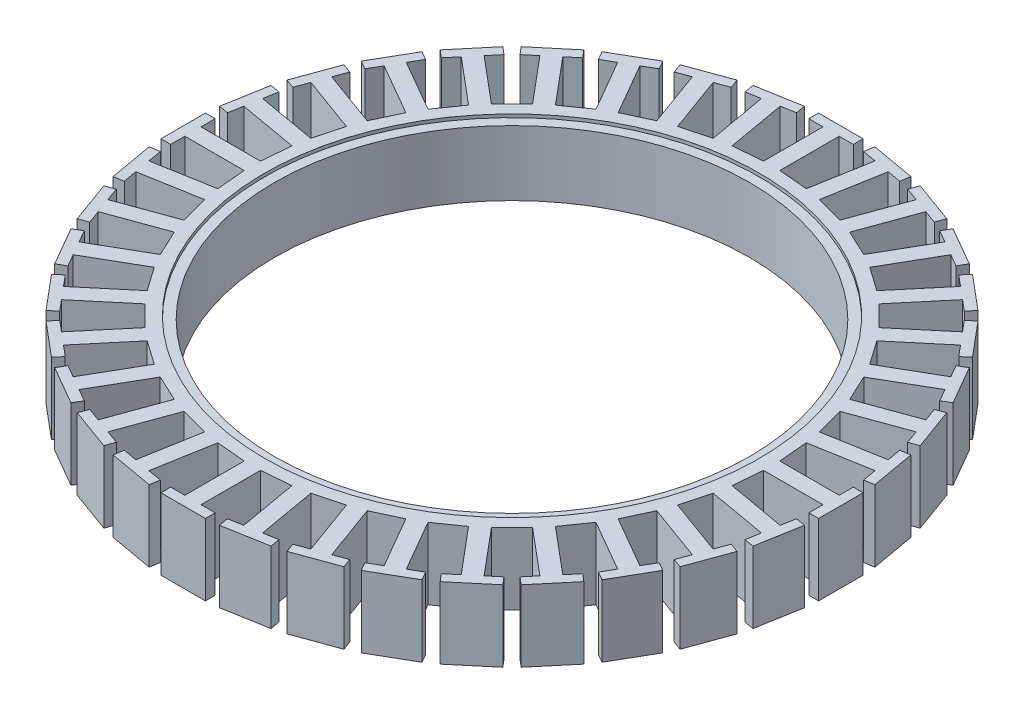
SolidWorks part; units mm, degrees
ref_plane "Front Plane" through (0, 0, 0) normal (0, 0, 1) x (1, 0, 0)
ref_plane "Top Plane" through (0, 0, 0) normal (0, 1, 0) x (1, 0, 0)
ref_plane "Right Plane" through (0, 0, 0) normal (1, 0, 0) x (0, 0, -1)
sketch "Sketch1" plane through (0, 0, 0) normal (0, 1, 0) x (1, 0, 0)
  circle A0 centre (0, 0) radius 29.25
  circle A1 centre (0, 0) radius 30.45
  dimension "D1" = 58.5
  dimension "D2" = 1.2
extrude "Boss-Extrude1" add sketch "Sketch1" along normal mid plane 8
sketch "Sketch2" plane through (0, 0, 0) normal (0, 1, 0) x (1, 0, 0)
  line L0 (0, 0) -> (0, 40.5) construction
  line L1 (-3.5433, 40.5) -> (-10.5222, 39.2694)
  line L2 (-10.5222, 39.2694) -> (-17.1814, 36.8457)
  line L3 (-17.1814, 36.8457) -> (-23.3186, 33.3024)
  line L4 (-23.3186, 33.3024) -> (-28.7472, 28.7472)
  line L5 (-28.7472, 28.7472) -> (-33.3024, 23.3186)
  line L6 (-33.3024, 23.3186) -> (-36.8457, 17.1814)
  line L7 (-36.8457, 17.1814) -> (-39.2694, 10.5222)
  line L8 (-39.2694, 10.5222) -> (-40.5, 3.5433)
  line L9 (-40.5, 3.5433) -> (-40.5, -3.5433)
  line L10 (-40.5, -3.5433) -> (-39.2694, -10.5222)
  line L11 (-39.2694, -10.5222) -> (-36.8457, -17.1814)
  line L12 (-36.8457, -17.1814) -> (-33.3024, -23.3186)
  line L13 (-33.3024, -23.3186) -> (-28.7472, -28.7472)
  line L14 (-28.7472, -28.7472) -> (-23.3186, -33.3024)
  line L15 (-23.3186, -33.3024) -> (-17.1814, -36.8457)
  line L16 (-17.1814, -36.8457) -> (-10.5222, -39.2694)
  line L17 (-10.5222, -39.2694) -> (-3.5433, -40.5)
  line L18 (-3.5433, -40.5) -> (3.5433, -40.5)
  line L19 (3.5433, -40.5) -> (10.5222, -39.2694)
  line L20 (10.5222, -39.2694) -> (17.1814, -36.8457)
  line L21 (17.1814, -36.8457) -> (23.3186, -33.3024)
  line L22 (23.3186, -33.3024) -> (28.7472, -28.7472)
  line L23 (28.7472, -28.7472) -> (33.3024, -23.3186)
  line L24 (33.3024, -23.3186) -> (36.8457, -17.1814)
  line L25 (36.8457, -17.1814) -> (39.2694, -10.5222)
  line L26 (39.2694, -10.5222) -> (40.5, -3.5433)
  line L27 (40.5, -3.5433) -> (40.5, 3.5433)
  line L28 (40.5, 3.5433) -> (39.2694, 10.5222)
  line L29 (39.2694, 10.5222) -> (36.8457, 17.1814)
  line L30 (36.8457, 17.1814) -> (33.3024, 23.3186)
  line L31 (33.3024, 23.3186) -> (28.7472, 28.7472)
  line L32 (28.7472, 28.7472) -> (23.3186, 33.3024)
  line L33 (23.3186, 33.3024) -> (17.1814, 36.8457)
  line L34 (17.1814, 36.8457) -> (10.5222, 39.2694)
  line L35 (10.5222, 39.2694) -> (3.5433, 40.5)
  line L36 (3.5433, 40.5) -> (-3.5433, 40.5)
  circle A1 centre (0, 0) radius 30.45
  circle A2 centre (0, 0) radius 40.5 construction
  circle A3 centre (0, 0) radius 30.45 construction
  dimension "D1" = 81
extrude "Boss-Extrude2" add sketch "Sketch2" along normal mid plane 8.8
sketch "Sketch4" plane through (0, 4.4, 0) normal (0, 1, 0) x (1, 0, 0)
  line L0 (0, 0) -> (0, 40.5) construction
  line L1 (3.5433, 40.5) -> (-3.5433, 40.5) construction
  line L2 (0, 0) -> (3.5433, 40.5) construction
  line L3 (1, 39.3) -> (2.7402, 39.3)
  line L4 (1, 39.3) -> (1, 31.9846)
  line L5 (10.5222, 39.2694) -> (3.5433, 40.5) construction
  line L6 (1, 31.9846) -> (4.5693, 31.6723)
  line L7 (4.5693, 31.6723) -> (5.8396, 38.8766)
  line L8 (2.7402, 39.3) -> (2.7402, 40.5)
  line L9 (2.7402, 40.5) -> (3.5433, 40.5)
  line L10 (3.5433, 40.5) -> (4.3341, 40.3606)
  line L11 (4.3341, 40.3606) -> (4.1258, 39.1788)
  line L12 (4.1258, 39.1788) -> (5.8396, 38.8766)
  line L13 (7.8092, 38.5293) -> (9.523, 38.2271)
  line L14 (7.8092, 38.5293) -> (6.5389, 31.325)
  line L15 (6.5389, 31.325) -> (9.9997, 30.3977)
  line L16 (9.9997, 30.3977) -> (12.5017, 37.2719)
  line L17 (9.523, 38.2271) -> (9.7314, 39.4089)
  line L18 (9.7314, 39.4089) -> (10.5222, 39.2694)
  line L19 (10.5222, 39.2694) -> (11.2768, 38.9948)
  line L20 (11.2768, 38.9948) -> (10.8664, 37.8671)
  line L21 (10.8664, 37.8671) -> (12.5017, 37.2719)
  line L22 (14.3811, 36.5879) -> (16.0164, 35.9927)
  line L23 (14.3811, 36.5879) -> (11.8791, 29.7136)
  line L24 (11.8791, 29.7136) -> (15.1263, 28.1994)
  line L25 (15.1263, 28.1994) -> (18.784, 34.5348)
  line L26 (16.0164, 35.9927) -> (16.4268, 37.1203)
  line L27 (16.4268, 37.1203) -> (17.1814, 36.8457)
  line L28 (17.1814, 36.8457) -> (17.8769, 36.4441)
  line L29 (17.8769, 36.4441) -> (17.2769, 35.4049)
  line L30 (17.2769, 35.4049) -> (18.784, 34.5348)
  line L31 (20.516, 33.5348) -> (22.0231, 32.6647)
  line L32 (20.516, 33.5348) -> (16.8583, 27.1994)
  line L33 (16.8583, 27.1994) -> (19.7932, 25.1444)
  line L34 (19.7932, 25.1444) -> (24.4955, 30.7483)
  line L35 (22.0231, 32.6647) -> (22.6231, 33.7039)
  line L36 (22.6231, 33.7039) -> (23.3186, 33.3024)
  line L37 (23.3186, 33.3024) -> (23.9338, 32.7862)
  line L38 (23.9338, 32.7862) -> (23.1624, 31.8669)
  line L39 (23.1624, 31.8669) -> (24.4955, 30.7483)
  line L40 (26.0276, 29.4628) -> (27.3607, 28.3442)
  line L41 (26.0276, 29.4628) -> (21.3253, 23.8588)
  line L42 (21.3253, 23.8588) -> (23.8588, 21.3253)
  line L43 (23.8588, 21.3253) -> (29.4628, 26.0276)
  line L44 (27.3607, 28.3442) -> (28.132, 29.2634)
  line L45 (28.132, 29.2634) -> (28.7472, 28.7472)
  line L46 (28.7472, 28.7472) -> (29.2634, 28.132)
  line L47 (29.2634, 28.132) -> (28.3442, 27.3607)
  line L48 (28.3442, 27.3607) -> (29.4628, 26.0276)
  line L49 (30.7483, 24.4955) -> (31.8669, 23.1624)
  line L50 (30.7483, 24.4955) -> (25.1444, 19.7932)
  line L51 (25.1444, 19.7932) -> (27.1994, 16.8583)
  line L52 (27.1994, 16.8583) -> (33.5348, 20.516)
  line L53 (31.8669, 23.1624) -> (32.7862, 23.9338)
  line L54 (32.7862, 23.9338) -> (33.3024, 23.3186)
  line L55 (33.3024, 23.3186) -> (33.7039, 22.6231)
  line L56 (33.7039, 22.6231) -> (32.6647, 22.0231)
  line L57 (32.6647, 22.0231) -> (33.5348, 20.516)
  line L58 (34.5348, 18.784) -> (35.4049, 17.2769)
  line L59 (34.5348, 18.784) -> (28.1994, 15.1263)
  line L60 (28.1994, 15.1263) -> (29.7136, 11.8791)
  line L61 (29.7136, 11.8791) -> (36.5879, 14.3811)
  line L62 (35.4049, 17.2769) -> (36.4441, 17.8769)
  line L63 (36.4441, 17.8769) -> (36.8457, 17.1814)
  line L64 (36.8457, 17.1814) -> (37.1203, 16.4268)
  line L65 (37.1203, 16.4268) -> (35.9927, 16.0164)
  line L66 (35.9927, 16.0164) -> (36.5879, 14.3811)
  line L67 (37.2719, 12.5017) -> (37.8671, 10.8664)
  line L68 (37.2719, 12.5017) -> (30.3977, 9.9997)
  line L69 (30.3977, 9.9997) -> (31.325, 6.5389)
  line L70 (31.325, 6.5389) -> (38.5293, 7.8092)
  line L71 (37.8671, 10.8664) -> (38.9948, 11.2768)
  line L72 (38.9948, 11.2768) -> (39.2694, 10.5222)
  line L73 (39.2694, 10.5222) -> (39.4089, 9.7314)
  line L74 (39.4089, 9.7314) -> (38.2271, 9.523)
  line L75 (38.2271, 9.523) -> (38.5293, 7.8092)
  line L76 (38.8766, 5.8396) -> (39.1788, 4.1258)
  line L77 (38.8766, 5.8396) -> (31.6723, 4.5693)
  line L78 (31.6723, 4.5693) -> (31.9846, 1)
  line L79 (31.9846, 1) -> (39.3, 1)
  line L80 (39.1788, 4.1258) -> (40.3606, 4.3341)
  line L81 (40.3606, 4.3341) -> (40.5, 3.5433)
  line L82 (40.5, 3.5433) -> (40.5, 2.7402)
  line L83 (40.5, 2.7402) -> (39.3, 2.7402)
  line L84 (39.3, 2.7402) -> (39.3, 1)
  line L85 (39.3, -1) -> (39.3, -2.7402)
  line L86 (39.3, -1) -> (31.9846, -1)
  line L87 (31.9846, -1) -> (31.6723, -4.5693)
  line L88 (31.6723, -4.5693) -> (38.8766, -5.8396)
  line L89 (39.3, -2.7402) -> (40.5, -2.7402)
  line L90 (40.5, -2.7402) -> (40.5, -3.5433)
  line L91 (40.5, -3.5433) -> (40.3606, -4.3341)
  line L92 (40.3606, -4.3341) -> (39.1788, -4.1258)
  line L93 (39.1788, -4.1258) -> (38.8766, -5.8396)
  line L94 (38.5293, -7.8092) -> (38.2271, -9.523)
  line L95 (38.5293, -7.8092) -> (31.325, -6.5389)
  line L96 (31.325, -6.5389) -> (30.3977, -9.9997)
  line L97 (30.3977, -9.9997) -> (37.2719, -12.5017)
  line L98 (38.2271, -9.523) -> (39.4089, -9.7314)
  line L99 (39.4089, -9.7314) -> (39.2694, -10.5222)
  line L100 (39.2694, -10.5222) -> (38.9948, -11.2768)
  line L101 (38.9948, -11.2768) -> (37.8671, -10.8664)
  line L102 (37.8671, -10.8664) -> (37.2719, -12.5017)
  line L103 (36.5879, -14.3811) -> (35.9927, -16.0164)
  line L104 (36.5879, -14.3811) -> (29.7136, -11.8791)
  line L105 (29.7136, -11.8791) -> (28.1994, -15.1263)
  line L106 (28.1994, -15.1263) -> (34.5348, -18.784)
  line L107 (35.9927, -16.0164) -> (37.1203, -16.4268)
  line L108 (37.1203, -16.4268) -> (36.8457, -17.1814)
  line L109 (36.8457, -17.1814) -> (36.4441, -17.8769)
  line L110 (36.4441, -17.8769) -> (35.4049, -17.2769)
  line L111 (35.4049, -17.2769) -> (34.5348, -18.784)
  line L112 (33.5348, -20.516) -> (32.6647, -22.0231)
  line L113 (33.5348, -20.516) -> (27.1994, -16.8583)
  line L114 (27.1994, -16.8583) -> (25.1444, -19.7932)
  line L115 (25.1444, -19.7932) -> (30.7483, -24.4955)
  line L116 (32.6647, -22.0231) -> (33.7039, -22.6231)
  line L117 (33.7039, -22.6231) -> (33.3024, -23.3186)
  line L118 (33.3024, -23.3186) -> (32.7862, -23.9338)
  line L119 (32.7862, -23.9338) -> (31.8669, -23.1624)
  line L120 (31.8669, -23.1624) -> (30.7483, -24.4955)
  line L121 (29.4628, -26.0276) -> (28.3442, -27.3607)
  line L122 (29.4628, -26.0276) -> (23.8588, -21.3253)
  line L123 (23.8588, -21.3253) -> (21.3253, -23.8588)
  line L124 (21.3253, -23.8588) -> (26.0276, -29.4628)
  line L125 (28.3442, -27.3607) -> (29.2634, -28.132)
  line L126 (29.2634, -28.132) -> (28.7472, -28.7472)
  line L127 (28.7472, -28.7472) -> (28.132, -29.2634)
  line L128 (28.132, -29.2634) -> (27.3607, -28.3442)
  line L129 (27.3607, -28.3442) -> (26.0276, -29.4628)
  line L130 (24.4955, -30.7483) -> (23.1624, -31.8669)
  line L131 (24.4955, -30.7483) -> (19.7932, -25.1444)
  line L132 (19.7932, -25.1444) -> (16.8583, -27.1994)
  line L133 (16.8583, -27.1994) -> (20.516, -33.5348)
  line L134 (23.1624, -31.8669) -> (23.9338, -32.7862)
  line L135 (23.9338, -32.7862) -> (23.3186, -33.3024)
  line L136 (23.3186, -33.3024) -> (22.6231, -33.7039)
  line L137 (22.6231, -33.7039) -> (22.0231, -32.6647)
  line L138 (22.0231, -32.6647) -> (20.516, -33.5348)
  line L139 (18.784, -34.5348) -> (17.2769, -35.4049)
  line L140 (18.784, -34.5348) -> (15.1263, -28.1994)
  line L141 (15.1263, -28.1994) -> (11.8791, -29.7136)
  line L142 (11.8791, -29.7136) -> (14.3811, -36.5879)
  line L143 (17.2769, -35.4049) -> (17.8769, -36.4441)
  line L144 (17.8769, -36.4441) -> (17.1814, -36.8457)
  line L145 (17.1814, -36.8457) -> (16.4268, -37.1203)
  line L146 (16.4268, -37.1203) -> (16.0164, -35.9927)
  line L147 (16.0164, -35.9927) -> (14.3811, -36.5879)
  line L148 (12.5017, -37.2719) -> (10.8664, -37.8671)
  line L149 (12.5017, -37.2719) -> (9.9997, -30.3977)
  line L150 (9.9997, -30.3977) -> (6.5389, -31.325)
  line L151 (6.5389, -31.325) -> (7.8092, -38.5293)
  line L152 (10.8664, -37.8671) -> (11.2768, -38.9948)
  line L153 (11.2768, -38.9948) -> (10.5222, -39.2694)
  line L154 (10.5222, -39.2694) -> (9.7314, -39.4089)
  line L155 (9.7314, -39.4089) -> (9.523, -38.2271)
  line L156 (9.523, -38.2271) -> (7.8092, -38.5293)
  line L157 (5.8396, -38.8766) -> (4.1258, -39.1788)
  line L158 (5.8396, -38.8766) -> (4.5693, -31.6723)
  line L159 (4.5693, -31.6723) -> (1, -31.9846)
  line L160 (1, -31.9846) -> (1, -39.3)
  line L161 (4.1258, -39.1788) -> (4.3341, -40.3606)
  line L162 (4.3341, -40.3606) -> (3.5433, -40.5)
  line L163 (3.5433, -40.5) -> (2.7402, -40.5)
  line L164 (2.7402, -40.5) -> (2.7402, -39.3)
  line L165 (2.7402, -39.3) -> (1, -39.3)
  line L166 (-1, -39.3) -> (-2.7402, -39.3)
  line L167 (-1, -39.3) -> (-1, -31.9846)
  line L168 (-1, -31.9846) -> (-4.5693, -31.6723)
  line L169 (-4.5693, -31.6723) -> (-5.8396, -38.8766)
  line L170 (-2.7402, -39.3) -> (-2.7402, -40.5)
  line L171 (-2.7402, -40.5) -> (-3.5433, -40.5)
  line L172 (-3.5433, -40.5) -> (-4.3341, -40.3606)
  line L173 (-4.3341, -40.3606) -> (-4.1258, -39.1788)
  line L174 (-4.1258, -39.1788) -> (-5.8396, -38.8766)
  line L175 (-7.8092, -38.5293) -> (-9.523, -38.2271)
  line L176 (-7.8092, -38.5293) -> (-6.5389, -31.325)
  line L177 (-6.5389, -31.325) -> (-9.9997, -30.3977)
  line L178 (-9.9997, -30.3977) -> (-12.5017, -37.2719)
  line L179 (-9.523, -38.2271) -> (-9.7314, -39.4089)
  line L180 (-9.7314, -39.4089) -> (-10.5222, -39.2694)
  line L181 (-10.5222, -39.2694) -> (-11.2768, -38.9948)
  line L182 (-11.2768, -38.9948) -> (-10.8664, -37.8671)
  line L183 (-10.8664, -37.8671) -> (-12.5017, -37.2719)
  line L184 (-14.3811, -36.5879) -> (-16.0164, -35.9927)
  line L185 (-14.3811, -36.5879) -> (-11.8791, -29.7136)
  line L186 (-11.8791, -29.7136) -> (-15.1263, -28.1994)
  line L187 (-15.1263, -28.1994) -> (-18.784, -34.5348)
  line L188 (-16.0164, -35.9927) -> (-16.4268, -37.1203)
  line L189 (-16.4268, -37.1203) -> (-17.1814, -36.8457)
  line L190 (-17.1814, -36.8457) -> (-17.8769, -36.4441)
  line L191 (-17.8769, -36.4441) -> (-17.2769, -35.4049)
  line L192 (-17.2769, -35.4049) -> (-18.784, -34.5348)
  line L193 (-20.516, -33.5348) -> (-22.0231, -32.6647)
  line L194 (-20.516, -33.5348) -> (-16.8583, -27.1994)
  line L195 (-16.8583, -27.1994) -> (-19.7932, -25.1444)
  line L196 (-19.7932, -25.1444) -> (-24.4955, -30.7483)
  line L197 (-22.0231, -32.6647) -> (-22.6231, -33.7039)
  line L198 (-22.6231, -33.7039) -> (-23.3186, -33.3024)
  line L199 (-23.3186, -33.3024) -> (-23.9338, -32.7862)
  line L200 (-23.9338, -32.7862) -> (-23.1624, -31.8669)
  line L201 (-23.1624, -31.8669) -> (-24.4955, -30.7483)
  line L202 (-26.0276, -29.4628) -> (-27.3607, -28.3442)
  line L203 (-26.0276, -29.4628) -> (-21.3253, -23.8588)
  line L204 (-21.3253, -23.8588) -> (-23.8588, -21.3253)
  line L205 (-23.8588, -21.3253) -> (-29.4628, -26.0276)
  line L206 (-27.3607, -28.3442) -> (-28.132, -29.2634)
  line L207 (-28.132, -29.2634) -> (-28.7472, -28.7472)
  line L208 (-28.7472, -28.7472) -> (-29.2634, -28.132)
  line L209 (-29.2634, -28.132) -> (-28.3442, -27.3607)
  line L210 (-28.3442, -27.3607) -> (-29.4628, -26.0276)
  line L211 (-30.7483, -24.4955) -> (-31.8669, -23.1624)
  line L212 (-30.7483, -24.4955) -> (-25.1444, -19.7932)
  line L213 (-25.1444, -19.7932) -> (-27.1994, -16.8583)
  line L214 (-27.1994, -16.8583) -> (-33.5348, -20.516)
  line L215 (-31.8669, -23.1624) -> (-32.7862, -23.9338)
  line L216 (-32.7862, -23.9338) -> (-33.3024, -23.3186)
  line L217 (-33.3024, -23.3186) -> (-33.7039, -22.6231)
  line L218 (-33.7039, -22.6231) -> (-32.6647, -22.0231)
  line L219 (-32.6647, -22.0231) -> (-33.5348, -20.516)
  line L220 (-34.5348, -18.784) -> (-35.4049, -17.2769)
  line L221 (-34.5348, -18.784) -> (-28.1994, -15.1263)
  line L222 (-28.1994, -15.1263) -> (-29.7136, -11.8791)
  line L223 (-29.7136, -11.8791) -> (-36.5879, -14.3811)
  line L224 (-35.4049, -17.2769) -> (-36.4441, -17.8769)
  line L225 (-36.4441, -17.8769) -> (-36.8457, -17.1814)
  line L226 (-36.8457, -17.1814) -> (-37.1203, -16.4268)
  line L227 (-37.1203, -16.4268) -> (-35.9927, -16.0164)
  line L228 (-35.9927, -16.0164) -> (-36.5879, -14.3811)
  line L229 (-37.2719, -12.5017) -> (-37.8671, -10.8664)
  line L230 (-37.2719, -12.5017) -> (-30.3977, -9.9997)
  line L231 (-30.3977, -9.9997) -> (-31.325, -6.5389)
  line L232 (-31.325, -6.5389) -> (-38.5293, -7.8092)
  line L233 (-37.8671, -10.8664) -> (-38.9948, -11.2768)
  line L234 (-38.9948, -11.2768) -> (-39.2694, -10.5222)
  line L235 (-39.2694, -10.5222) -> (-39.4089, -9.7314)
  line L236 (-39.4089, -9.7314) -> (-38.2271, -9.523)
  line L237 (-38.2271, -9.523) -> (-38.5293, -7.8092)
  line L238 (-38.8766, -5.8396) -> (-39.1788, -4.1258)
  line L239 (-38.8766, -5.8396) -> (-31.6723, -4.5693)
  line L240 (-31.6723, -4.5693) -> (-31.9846, -1)
  line L241 (-31.9846, -1) -> (-39.3, -1)
  line L242 (-39.1788, -4.1258) -> (-40.3606, -4.3341)
  line L243 (-40.3606, -4.3341) -> (-40.5, -3.5433)
  line L244 (-40.5, -3.5433) -> (-40.5, -2.7402)
  line L245 (-40.5, -2.7402) -> (-39.3, -2.7402)
  line L246 (-39.3, -2.7402) -> (-39.3, -1)
  line L247 (-39.3, 1) -> (-39.3, 2.7402)
  line L248 (-39.3, 1) -> (-31.9846, 1)
  line L249 (-31.9846, 1) -> (-31.6723, 4.5693)
  line L250 (-31.6723, 4.5693) -> (-38.8766, 5.8396)
  line L251 (-39.3, 2.7402) -> (-40.5, 2.7402)
  line L252 (-40.5, 2.7402) -> (-40.5, 3.5433)
  line L253 (-40.5, 3.5433) -> (-40.3606, 4.3341)
  line L254 (-40.3606, 4.3341) -> (-39.1788, 4.1258)
  line L255 (-39.1788, 4.1258) -> (-38.8766, 5.8396)
  line L256 (-38.5293, 7.8092) -> (-38.2271, 9.523)
  line L257 (-38.5293, 7.8092) -> (-31.325, 6.5389)
  line L258 (-31.325, 6.5389) -> (-30.3977, 9.9997)
  line L259 (-30.3977, 9.9997) -> (-37.2719, 12.5017)
  line L260 (-38.2271, 9.523) -> (-39.4089, 9.7314)
  line L261 (-39.4089, 9.7314) -> (-39.2694, 10.5222)
  line L262 (-39.2694, 10.5222) -> (-38.9948, 11.2768)
  line L263 (-38.9948, 11.2768) -> (-37.8671, 10.8664)
  line L264 (-37.8671, 10.8664) -> (-37.2719, 12.5017)
  line L265 (-36.5879, 14.3811) -> (-35.9927, 16.0164)
  line L266 (-36.5879, 14.3811) -> (-29.7136, 11.8791)
  line L267 (-29.7136, 11.8791) -> (-28.1994, 15.1263)
  line L268 (-28.1994, 15.1263) -> (-34.5348, 18.784)
  line L269 (-35.9927, 16.0164) -> (-37.1203, 16.4268)
  line L270 (-37.1203, 16.4268) -> (-36.8457, 17.1814)
  line L271 (-36.8457, 17.1814) -> (-36.4441, 17.8769)
  line L272 (-36.4441, 17.8769) -> (-35.4049, 17.2769)
  line L273 (-35.4049, 17.2769) -> (-34.5348, 18.784)
  line L274 (-33.5348, 20.516) -> (-32.6647, 22.0231)
  line L275 (-33.5348, 20.516) -> (-27.1994, 16.8583)
  line L276 (-27.1994, 16.8583) -> (-25.1444, 19.7932)
  line L277 (-25.1444, 19.7932) -> (-30.7483, 24.4955)
  line L278 (-32.6647, 22.0231) -> (-33.7039, 22.6231)
  line L279 (-33.7039, 22.6231) -> (-33.3024, 23.3186)
  line L280 (-33.3024, 23.3186) -> (-32.7862, 23.9338)
  line L281 (-32.7862, 23.9338) -> (-31.8669, 23.1624)
  line L282 (-31.8669, 23.1624) -> (-30.7483, 24.4955)
  line L283 (-29.4628, 26.0276) -> (-28.3442, 27.3607)
  line L284 (-29.4628, 26.0276) -> (-23.8588, 21.3253)
  line L285 (-23.8588, 21.3253) -> (-21.3253, 23.8588)
  line L286 (-21.3253, 23.8588) -> (-26.0276, 29.4628)
  line L287 (-28.3442, 27.3607) -> (-29.2634, 28.132)
  line L288 (-29.2634, 28.132) -> (-28.7472, 28.7472)
  line L289 (-28.7472, 28.7472) -> (-28.132, 29.2634)
  line L290 (-28.132, 29.2634) -> (-27.3607, 28.3442)
  line L291 (-27.3607, 28.3442) -> (-26.0276, 29.4628)
  line L292 (-24.4955, 30.7483) -> (-23.1624, 31.8669)
  line L293 (-24.4955, 30.7483) -> (-19.7932, 25.1444)
  line L294 (-19.7932, 25.1444) -> (-16.8583, 27.1994)
  line L295 (-16.8583, 27.1994) -> (-20.516, 33.5348)
  line L296 (-23.1624, 31.8669) -> (-23.9338, 32.7862)
  line L297 (-23.9338, 32.7862) -> (-23.3186, 33.3024)
  line L298 (-23.3186, 33.3024) -> (-22.6231, 33.7039)
  line L299 (-22.6231, 33.7039) -> (-22.0231, 32.6647)
  line L300 (-22.0231, 32.6647) -> (-20.516, 33.5348)
  line L301 (-18.784, 34.5348) -> (-17.2769, 35.4049)
  line L302 (-18.784, 34.5348) -> (-15.1263, 28.1994)
  line L303 (-15.1263, 28.1994) -> (-11.8791, 29.7136)
  line L304 (-11.8791, 29.7136) -> (-14.3811, 36.5879)
  line L305 (-17.2769, 35.4049) -> (-17.8769, 36.4441)
  line L306 (-17.8769, 36.4441) -> (-17.1814, 36.8457)
  line L307 (-17.1814, 36.8457) -> (-16.4268, 37.1203)
  line L308 (-16.4268, 37.1203) -> (-16.0164, 35.9927)
  line L309 (-16.0164, 35.9927) -> (-14.3811, 36.5879)
  line L310 (-12.5017, 37.2719) -> (-10.8664, 37.8671)
  line L311 (-12.5017, 37.2719) -> (-9.9997, 30.3977)
  line L312 (-9.9997, 30.3977) -> (-6.5389, 31.325)
  line L313 (-6.5389, 31.325) -> (-7.8092, 38.5293)
  line L314 (-10.8664, 37.8671) -> (-11.2768, 38.9948)
  line L315 (-11.2768, 38.9948) -> (-10.5222, 39.2694)
  line L316 (-10.5222, 39.2694) -> (-9.7314, 39.4089)
  line L317 (-9.7314, 39.4089) -> (-9.523, 38.2271)
  line L318 (-9.523, 38.2271) -> (-7.8092, 38.5293)
  line L319 (-5.8396, 38.8766) -> (-4.1258, 39.1788)
  line L320 (-5.8396, 38.8766) -> (-4.5693, 31.6723)
  line L321 (-4.5693, 31.6723) -> (-1, 31.9846)
  line L322 (-1, 31.9846) -> (-1, 39.3)
  line L323 (-4.1258, 39.1788) -> (-4.3341, 40.3606)
  line L324 (-4.3341, 40.3606) -> (-3.5433, 40.5)
  line L325 (-3.5433, 40.5) -> (-2.7402, 40.5)
  line L326 (-2.7402, 40.5) -> (-2.7402, 39.3)
  line L327 (-2.7402, 39.3) -> (-1, 39.3)
  circle A0 centre (0, 0) radius 30.45 construction
  point P337 (0, 0)
  dimension "D1" = 31.95
  dimension "D2" = 1.2
  dimension "D3" = 1
  dimension "D4" = 1.6
  dimension "D5" = 36
extrude "Cut-Extrude1" cut sketch "Sketch4" against normal up to surface (8.8 mm away) up to face at (0, -4.4, 0)
